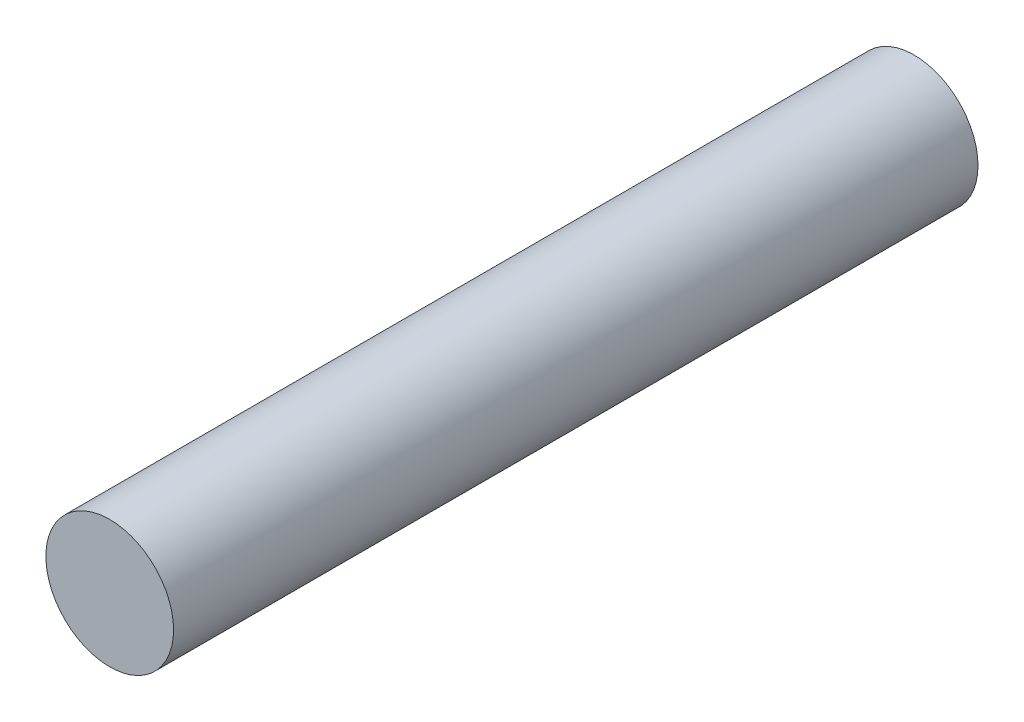
SolidWorks part; units mm, degrees
ref_plane "前基準面" through (0, 0, 0) normal (0, 0, 1) x (1, 0, 0)
ref_plane "上基準面" through (0, 0, 0) normal (0, 1, 0) x (1, 0, 0)
ref_plane "右基準面" through (0, 0, 0) normal (1, 0, 0) x (0, 0, -1)
sketch "草圖1" plane through (0, 0, 0) normal (0, 0, 1) x (1, 0, 0)
  circle A0 centre (0, 0) radius 1.5875
  dimension "D1" = 3.175
extrude "填料-伸長1" add sketch "草圖1" along normal blind 20
